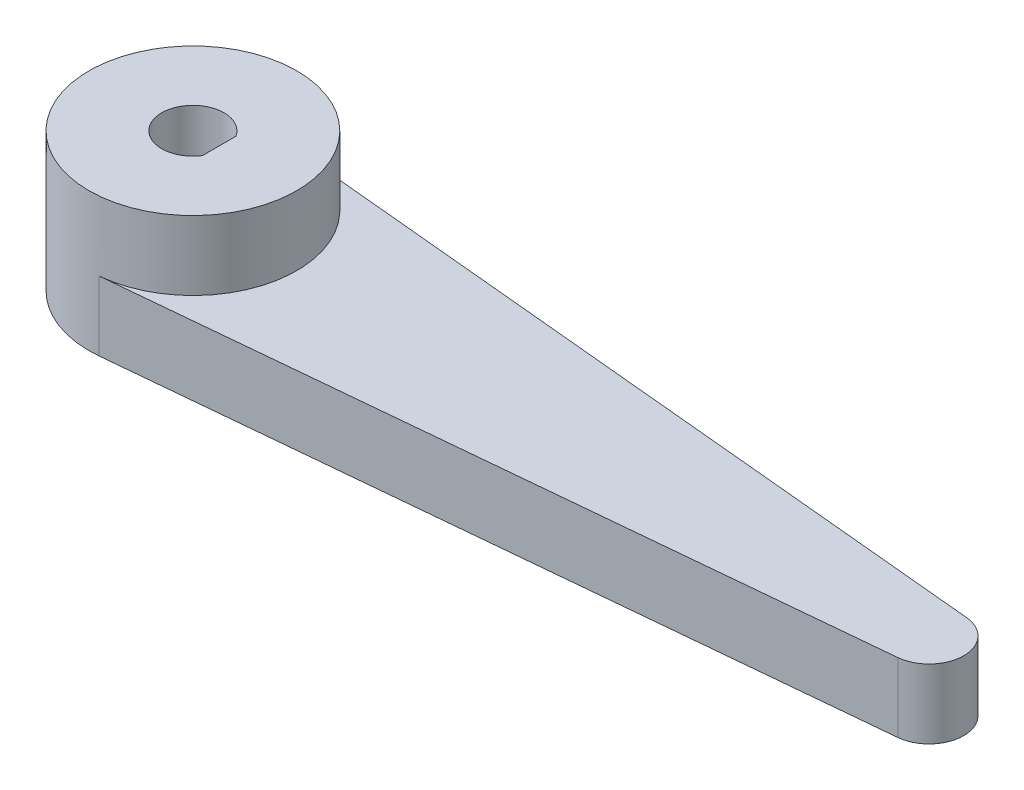
SolidWorks part; units mm, degrees
ref_plane "前视基准面" through (0, 0, 0) normal (0, 0, 1) x (1, 0, 0)
ref_plane "上视基准面" through (0, 0, 0) normal (0, 1, 0) x (1, 0, 0)
ref_plane "右视基准面" through (0, 0, 0) normal (1, 0, 0) x (0, 0, -1)
sketch "草图1" plane through (0, 0, 0) normal (0, 1, 0) x (1, 0, 0)
  line L0 (0, 0) -> (53.1451, 0) construction
  line L1 (0.7056, 7.4667) -> (53.3803, 2.4889)
  line L2 (0.7056, -7.4667) -> (53.3803, -2.4889)
  arc A0 (0.7056, 7.4667) -> (0.7056, -7.4667) centre (0, 0) ccw
  arc A1 (53.3803, -2.4889) -> (53.3803, 2.4889) centre (53.1451, 0) ccw
  dimension "D1" = 15
  dimension "D2" = 5
extrude "凸台-拉伸1" add sketch "草图1" along normal blind 5
sketch "草图2" plane through (0, 5, 0) normal (0, 1, 0) x (1, 0, 0)
  circle A0 centre (0, 0) radius 7.5
  arc A1 (0.7056, 7.4667) -> (0.7056, -7.4667) centre (0, 0) ccw construction
extrude "凸台-拉伸2" add sketch "草图2" along normal blind 5
sketch "草图3" plane through (0, 10, 0) normal (0, 1, 0) x (1, 0, 0)
  line L0 (1.8974, 1.2093) -> (1.8974, -1.2093)
  arc A0 (1.8974, 1.2093) -> (1.8974, -1.2093) centre (0, 0) ccw
  dimension "D1" = 4.5
extrude "切除-拉伸1" cut sketch "草图3" against normal through all
